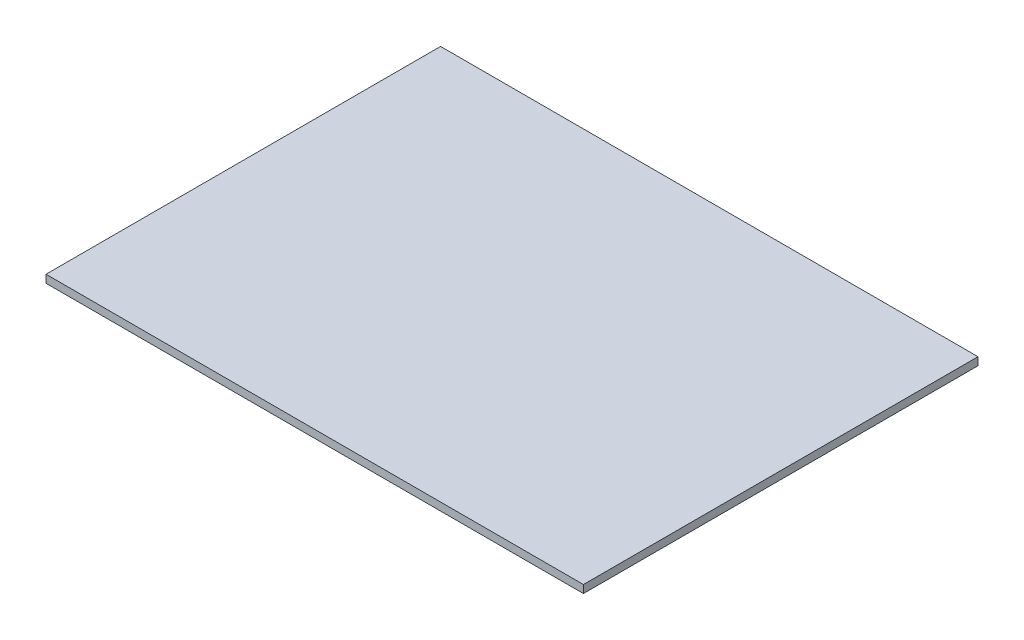
SolidWorks part; units mm, degrees
ref_plane "Front Plane" through (0, 0, 0) normal (0, 0, 1) x (1, 0, 0)
ref_plane "Top Plane" through (0, 0, 0) normal (0, 1, 0) x (1, 0, 0)
ref_plane "Right Plane" through (0, 0, 0) normal (1, 0, 0) x (0, 0, -1)
sketch "Sketch1" plane through (0, 0, 0) normal (0, 1, 0) x (1, 0, 0)
  line L1 (0, 0) -> (173.8, 0)
  line L2 (0, 0) -> (0, 127.6)
  line L3 (0, 127.6) -> (173.8, 127.6)
  line L4 (173.8, 0) -> (173.8, 127.6)
  dimension "D1" = 173.8
  dimension "D2" = 127.6
extrude "Boss-Extrude1" add sketch "Sketch1" along normal blind 2.54
